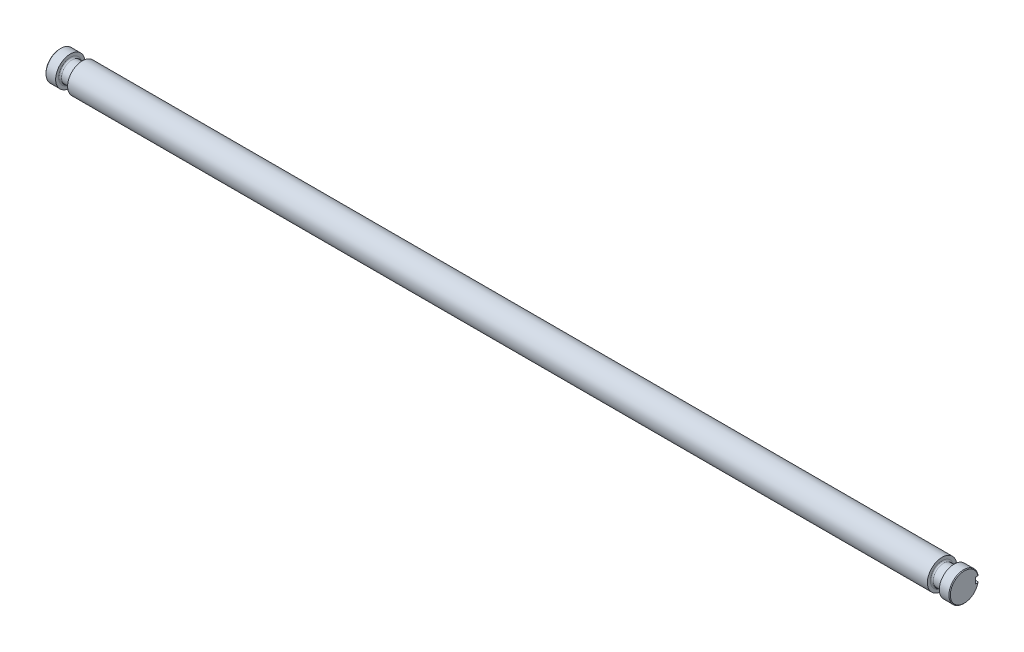
SolidWorks part; units mm, degrees
ref_plane "Front Plane" through (0, 0, 0) normal (0, 0, 1) x (1, 0, 0)
ref_plane "Top Plane" through (0, 0, 0) normal (0, 1, 0) x (1, 0, 0)
ref_plane "Right Plane" through (0, 0, 0) normal (1, 0, 0) x (0, 0, -1)
sketch "Sketch1" plane through (0, 0, 0) normal (0, 1, 0) x (1, 0, 0)
  line L0 (-976.376, 0) -> (-976.376, 31.7309)
  line L1 (-976.376, 31.7309) -> (-954.024, 31.7309)
  line L2 (-954.024, 31.7309) -> (-954.024, 22.0218)
  line L3 (-954.024, 22.0218) -> (-928.2176, 22.0218)
  line L4 (-928.2176, 22.0218) -> (-928.2176, 31.7309)
  line L5 (-928.2176, 31.7309) -> (928.3446, 31.7309)
  line L6 (928.3446, 31.7309) -> (928.3446, 22.0218)
  line L7 (928.3446, 22.0218) -> (954.151, 22.0218)
  line L8 (954.151, 22.0218) -> (954.151, 31.7309)
  line L9 (954.151, 31.7309) -> (976.376, 31.7309)
  line L10 (976.376, 31.7309) -> (976.376, 0)
  line L11 (976.376, 0) -> (-976.376, 0)
  line L12 (-1001.776, 0) -> (1001.776, 0) construction
  point P14 (0, 0)
  dimension "D1" = 22.225
  dimension "D2" = 48.0314
  dimension "D3" = 1904.5936
  dimension "D4" = 1930.4
  dimension "D5" = 1952.752
  dimension "D6" = 9.7092
  dimension "D7" = 31.7309
revolve "Revolve1" add sketch "Sketch1" angle 360 about L12
sketch "Sketch2" plane through (0, 0, 0) normal (1, 0, 0) x (0, 0, -1)
  line L1 (24.6062, -6.35) -> (88.0682, -6.35)
  line L2 (24.6062, -6.35) -> (24.6062, 6.35)
  line L3 (24.6062, 6.35) -> (88.0682, 6.35)
  line L4 (88.0682, -6.35) -> (88.0682, 6.35)
  point P8 (0, 0)
  dimension "D1" = 63.4619
  dimension "D2" = 12.7
  dimension "D3" = 88.0682
  dimension "D4" = 6.35
extrude "Cut-Extrude2" cut sketch "Sketch2" along normal blind 1997.456 from offset 998.728
fillet "Fillet1" radius 3.175 4 edges at (954.151, 0, 22.0218) (928.3446, 0, 22.0218) (-928.2176, 0, 22.0218) (-954.024, 0, 22.0218)
chamfer "Chamfer1" distance 1.524 angle 45 2 edges at (976.376, 0, 31.7309) (-976.376, 0, 31.7309)
